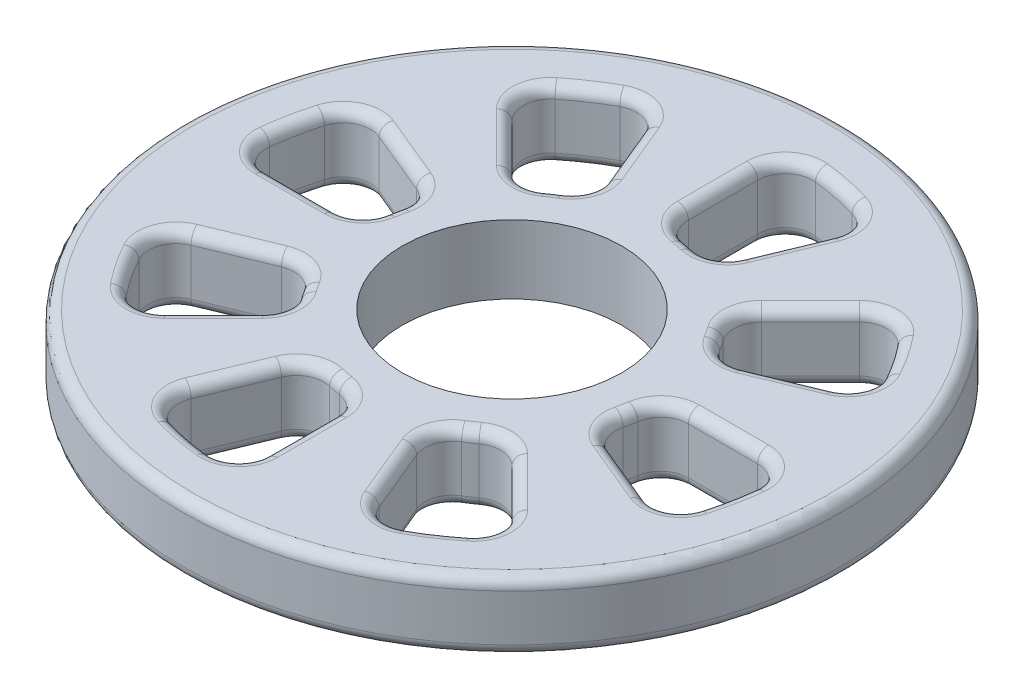
SolidWorks part; units mm, degrees
ref_plane "Front Plane" through (0, 0, 0) normal (0, 0, 1) x (1, 0, 0)
ref_plane "Top Plane" through (0, 0, 0) normal (0, 1, 0) x (1, 0, 0)
ref_plane "Right Plane" through (0, 0, 0) normal (1, 0, 0) x (0, 0, -1)
sketch "Sketch1" plane through (0, 0, 0) normal (0, 1, 0) x (1, 0, 0)
  line L0 (0, 11) -> (0, 20)
  line L1 (4.2095, 10.1627) -> (7.6537, 18.4776)
  line L2 (7.7782, 7.7782) -> (14.1421, 14.1421)
  line L3 (10.1627, 4.2095) -> (18.4776, 7.6537)
  line L4 (11, 0) -> (20, 0)
  line L5 (10.1627, -4.2095) -> (18.4776, -7.6537)
  line L6 (7.7782, -7.7782) -> (14.1421, -14.1421)
  line L7 (4.2095, -10.1627) -> (7.6537, -18.4776)
  line L8 (0, -11) -> (0, -20)
  line L9 (-4.2095, -10.1627) -> (-7.6537, -18.4776)
  line L10 (-7.7782, -7.7782) -> (-14.1421, -14.1421)
  line L11 (-10.1627, -4.2095) -> (-18.4776, -7.6537)
  line L12 (-11, 0) -> (-20, 0)
  line L13 (-10.1627, 4.2095) -> (-18.4776, 7.6537)
  line L14 (-7.7782, 7.7782) -> (-14.1421, 14.1421)
  line L15 (-4.2095, 10.1627) -> (-7.6537, 18.4776)
  arc A0 (7.6537, 18.4776) -> (0, 20) centre (0, 0) ccw
  circle A1 centre (0, 0) radius 24
  arc A2 (-10.1627, 4.2095) -> (-11, 0) centre (0, 0) ccw
  arc A3 (18.4776, 7.6537) -> (14.1421, 14.1421) centre (0, 0) ccw
  circle A4 centre (0, 0) radius 20 construction
  arc A5 (18.4776, -7.6537) -> (20, 0) centre (0, 0) ccw
  arc A6 (7.6537, -18.4776) -> (14.1421, -14.1421) centre (0, 0) ccw
  arc A7 (-7.6537, -18.4776) -> (0, -20) centre (0, 0) ccw
  arc A8 (-18.4776, -7.6537) -> (-14.1421, -14.1421) centre (0, 0) ccw
  arc A9 (-18.4776, 7.6537) -> (-20, 0) centre (0, 0) ccw
  arc A10 (-7.6537, 18.4776) -> (-14.1421, 14.1421) centre (0, 0) ccw
  circle A11 centre (0, 0) radius 8
  arc A12 (-4.2095, 10.1627) -> (-7.7782, 7.7782) centre (0, 0) ccw
  arc A13 (4.2095, 10.1627) -> (0, 11) centre (0, 0) ccw
  arc A14 (10.1627, 4.2095) -> (7.7782, 7.7782) centre (0, 0) ccw
  arc A15 (10.1627, -4.2095) -> (11, 0) centre (0, 0) ccw
  arc A16 (4.2095, -10.1627) -> (7.7782, -7.7782) centre (0, 0) ccw
  arc A17 (-4.2095, -10.1627) -> (0, -11) centre (0, 0) ccw
  arc A18 (-10.1627, -4.2095) -> (-7.7782, -7.7782) centre (0, 0) ccw
  point P8 (23.9076, 7.3093)
  point P41 (0, 0)
  dimension "D1" = 40
  dimension "D3" = 22
  dimension "D5" = 16
  dimension "D2" = 4
  dimension "D4" = 16
extrude "Boss-Extrude1" add sketch "Sketch1" along normal blind 5
fillet "Fillet1" radius 2 32 edges at (-7.6537, 2.5, -18.4776) (-14.1421, 2.5, -14.1421) (-7.7782, 2.5, -7.7782) (-4.2095, 2.5, -10.1627) (-18.4776, 2.5, -7.6537) (-20, 2.5, 0) (-11, 2.5, 0) (-10.1627, 2.5, -4.2095) (-18.4776, 2.5, 7.6537) (-14.1421, 2.5, 14.1421) (-7.7782, 2.5, 7.7782) (-10.1627, 2.5, 4.2095) (-7.6537, 2.5, 18.4776) (0, 2.5, 20) (-4.2095, 2.5, 10.1627) (7.6537, 2.5, 18.4776) (14.1421, 2.5, 14.1421) (7.7782, 2.5, 7.7782) (4.2095, 2.5, 10.1627) (18.4776, 2.5, 7.6537) (20, 2.5, 0) (11, 2.5, 0) (10.1627, 2.5, 4.2095) (18.4776, 2.5, -7.6537) (14.1421, 2.5, -14.1421) (7.7782, 2.5, -7.7782) (10.1627, 2.5, -4.2095) (7.6537, 2.5, -18.4776) (0, 2.5, -20) (0, 2.5, -11) (4.2095, 2.5, -10.1627) (0, 2.5, 11)
fillet "Fillet2" radius 0.8 2 edges at (0, 5, 24) (0, 0, 24)
fillet "Fillet3" radius 0.8 71 edges at (-13.2318, 0, -14.1746) (-4.8621, 0, -10.4816) (-6.1113, 0, -9.1462) (-10.866, 0, -10.866) (-16.6294, 0, 11.1114) (-17.649, 0, 8.032) (-14.1972, 0, 5.8807) (-10.866, 0, 10.866) (8.032, 0, 17.649) (5.8807, 0, 14.1972) (6.1113, 0, 9.1462) (10.866, 0, 10.866) (17.649, 0, -8.032) (9.1462, 0, -6.1113) (8.5031, 0, -7.823) (6.8002, 0, -18.1592) (3.9735, 0, -10.8496) (0.4809, 0, -11.5443) (0, 0, -15.3669) (18.1592, 0, 6.8002) (14.1972, 0, 5.8807) (10.7886, 0, 2.146) (-3.9018, 0, 19.6157) (-5.8807, 0, 14.1972) (-2.146, 0, 10.7886) (-0.4809, 0, 11.5443) (0, 0, 15.3669) (-19.3793, 0, -0.6667) (-19.6157, 0, -3.9018) (-18.1592, 0, -6.8002) (-11.5443, 0, -0.4809) (-15.3669, 0, 0) (15.3669, 0, 0) (-10.866, 5, -10.866) (-7.823, 5, -8.5031) (-6.1113, 5, -9.1462) (-5.8807, 5, -14.1972) (-18.1592, 5, -6.8002) (-19.6157, 5, -3.9018) (-15.3669, 5, 0) (-11.5443, 5, -0.4809) (-10.7886, 5, -2.146) (-10.8496, 5, -3.9735) (-17.649, 5, 8.032) (-10.866, 5, 10.866) (-8.5031, 5, 7.823) (-9.1462, 5, 6.1113) (-14.1972, 5, 5.8807) (-3.9018, 5, 19.6157) (0, 5, 15.3669) (-0.4809, 5, 11.5443) (-3.9735, 5, 10.8496) (8.032, 5, 17.649) (11.1114, 5, 16.6294) (10.866, 5, 10.866) (6.1113, 5, 9.1462) (4.8621, 5, 10.4816) (5.8807, 5, 14.1972) (18.1592, 5, 6.8002) (19.6157, 5, 3.9018) (10.7886, 5, 2.146) (17.649, 5, -8.032) (10.866, 5, -10.866) (8.5031, 5, -7.823) (9.1462, 5, -6.1113) (10.4816, 5, -4.8621) (0, 5, -15.3669) (0.4809, 5, -11.5443) (2.146, 5, -10.7886) (3.9735, 5, -10.8496) (14.1972, 5, -5.8807)
